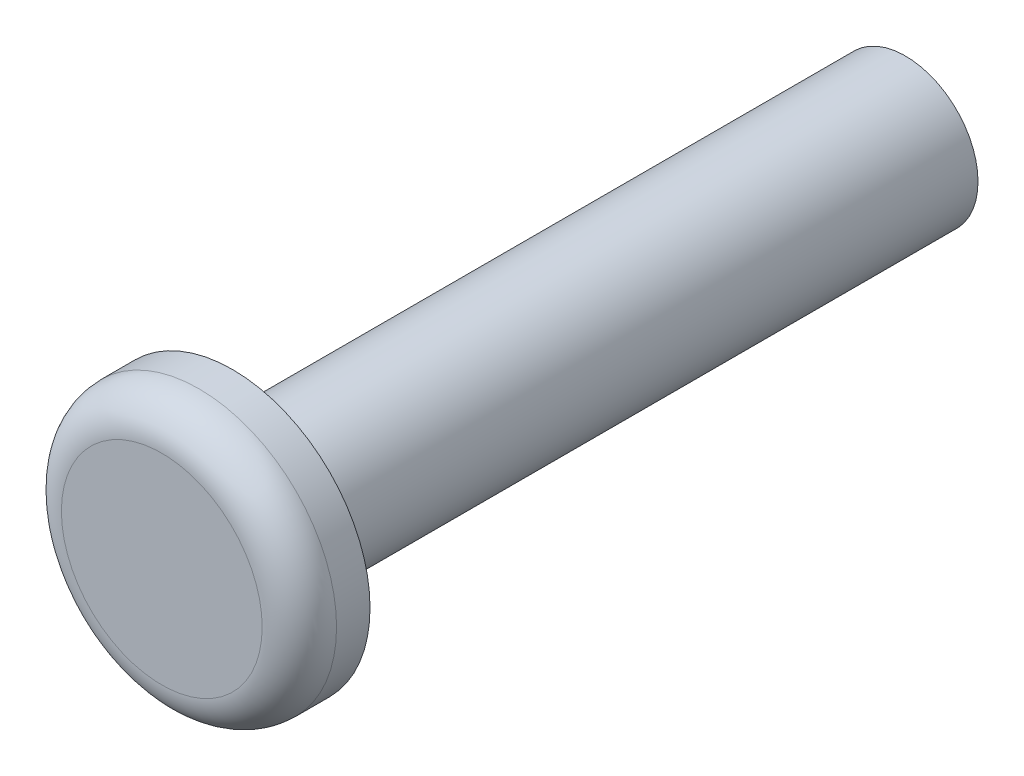
SolidWorks part; units mm, degrees
ref_plane "Front Plane" through (0, 0, 0) normal (0, 0, 1) x (1, 0, 0)
ref_plane "Top Plane" through (0, 0, 0) normal (0, 1, 0) x (1, 0, 0)
ref_plane "Right Plane" through (0, 0, 0) normal (1, 0, 0) x (0, 0, -1)
sketch "Sketch1" plane through (0, 0, 0) normal (1, 0, 0) x (0, 0, -1)
  line L0 (1.9, 1.95) -> (1.9, 3.7)
  line L1 (0, 0) -> (20, 0)
  line L3 (1.9, 1.95) -> (20, 1.95)
  line L4 (20, 0) -> (20, 1.95)
  line L5 (1.9, 3.7) -> (0, 3.7)
  line L6 (0, 3.7) -> (0, 0)
  dimension "D1" = 20
  dimension "D2" = 1.95
  dimension "D3" = 3.7
  dimension "D4" = 1.9
revolve "Revolve1" add sketch "Sketch1" angle 360 about L1
fillet "Fillet1" radius 1 1 edges at (3.7, 0, 0)
